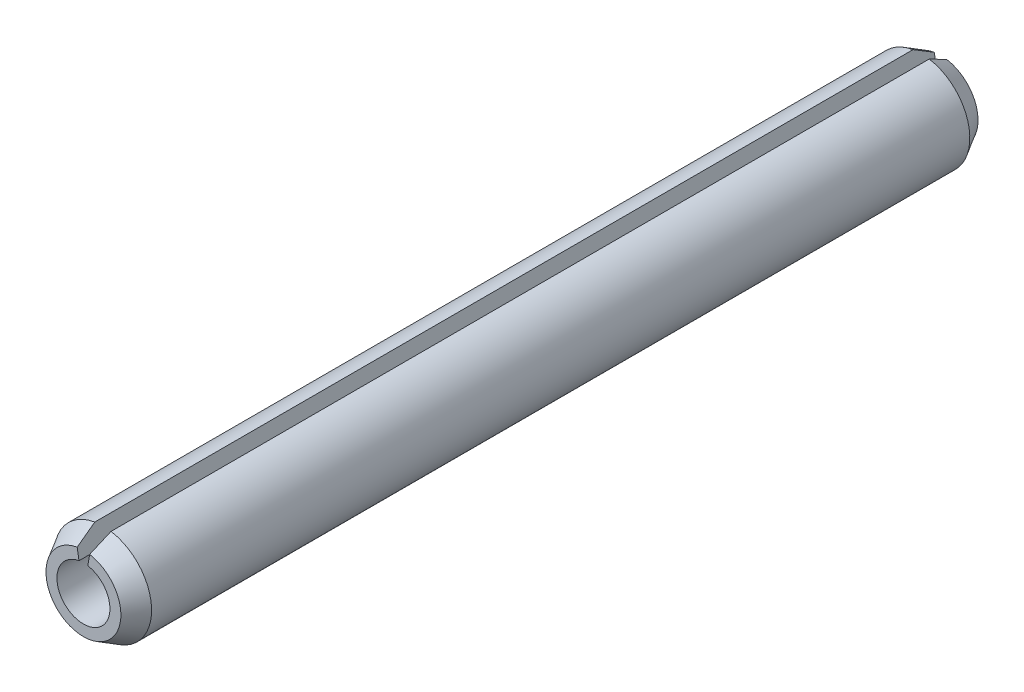
SolidWorks part; units mm, degrees
ref_plane "Front" through (0, 0, 0) normal (0, 0, 1) x (1, 0, 0)
ref_plane "Base" through (0, 0, 0) normal (0, 1, 0) x (1, 0, 0)
ref_plane "Side" through (0, 0, 0) normal (1, 0, 0) x (0, 0, -1)
sketch "Sketch1" plane through (0, 0, 0) normal (0, 0, 1) x (1, 0, 0)
  line L2 (0, 0) -> (0, 1.25) construction
  arc A0 (-0.2083, 1.2325) -> (0.2083, 1.2325) centre (0, 0) ccw
extrude "Base-Extrude-Thin" add sketch "Sketch1" along normal mid plane 22 thin thin type one direction reverse wall 0.57
chamfer "Chamfer1" distance 0.5 angle 30 2 edges at (0, -1.25, 11) (0, -1.25, -11)
equation "\"D1@Sketch1\"=\"NOMDIA@Sketch1\"/6"
